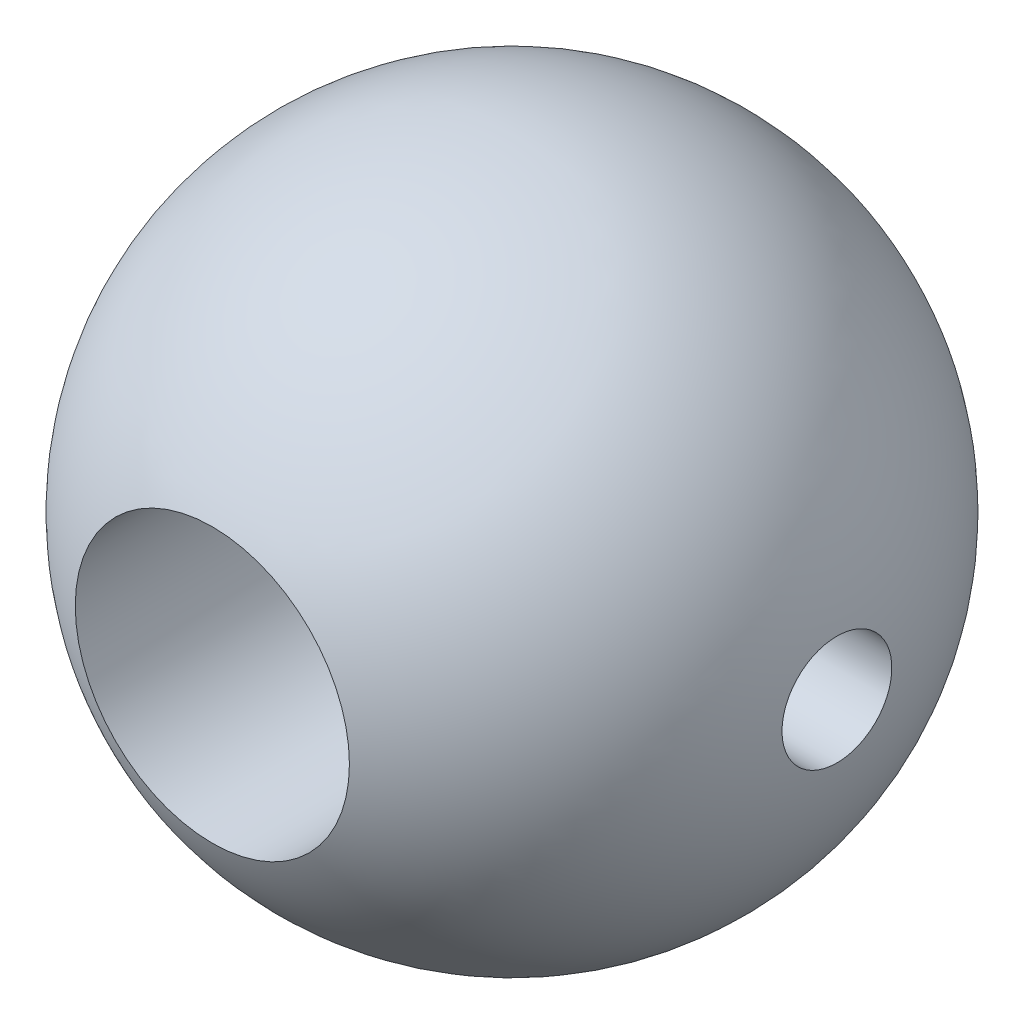
SolidWorks part; units mm, degrees
ref_plane "Front Plane" through (0, 0, 0) normal (0, 0, 1) x (1, 0, 0)
ref_plane "Top Plane" through (0, 0, 0) normal (0, 1, 0) x (1, 0, 0)
ref_plane "Right Plane" through (0, 0, 0) normal (1, 0, 0) x (0, 0, -1)
sketch "Sketch1" plane through (0, 0, 0) normal (0, 1, 0) x (1, 0, 0)
  line L0 (0, 15.8555) -> (0, -17.7872) construction
  line L1 (3.9624, 8.6617) -> (3.9624, -8.6617)
  arc A0 (3.9624, -8.6617) -> (3.9624, 8.6617) centre (0, 0) ccw
  dimension "D1" = 9.525
  dimension "D2" = 3.9624
revolve "Revolve1" add sketch "Sketch1" angle 360 about L0
sketch "Sketch2" plane through (0, 0, 0) normal (0, 1, 0) x (1, 0, 0)
  line L5 (-13.1037, 1.5875) -> (12.3929, 1.5875)
  line L6 (-13.1037, 1.5875) -> (-13.1037, 0)
  line L7 (-13.1037, 0) -> (12.3929, 0)
  line L8 (12.3929, 1.5875) -> (12.3929, 0)
  dimension "D1" = 1.5875
revolve "Cut-Revolve1" cut sketch "Sketch2" angle 360 about L7
